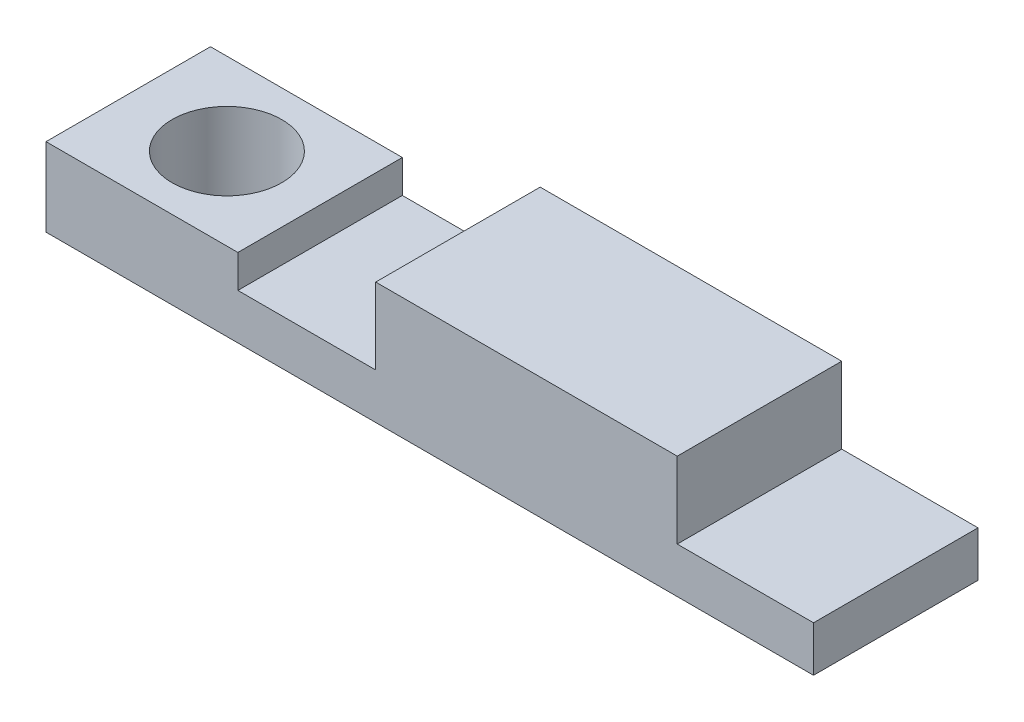
SolidWorks part; units mm, degrees
ref_plane "Front Plane" through (0, 0, 0) normal (0, 0, 1) x (1, 0, 0)
ref_plane "Top Plane" through (0, 0, 0) normal (0, 1, 0) x (1, 0, 0)
ref_plane "Right Plane" through (0, 0, 0) normal (1, 0, 0) x (0, 0, -1)
sketch "Sketch1" plane through (0, 0, 0) normal (0, 1, 0) x (1, 0, 0)
  line L1 (0, 0) -> (140, 0)
  line L2 (0, 0) -> (0, 30)
  line L3 (0, 30) -> (140, 30)
  line L4 (140, 0) -> (140, 30)
  dimension "D1" = 140
  dimension "D2" = 30
extrude "Boss-Extrude1" add sketch "Sketch1" along normal blind 8.3
sketch "Sketch3" plane through (0, 8.3, 0) normal (0, 1, 0) x (1, 0, 0)
  line L0 (140, 30) -> (0, 30) construction
  line L1 (0, 0) -> (35, 0)
  line L2 (0, 0) -> (0, 30)
  line L3 (0, 30) -> (35, 30)
  line L4 (35, 0) -> (35, 30)
  dimension "D1" = 35
extrude "Boss-Extrude2" add sketch "Sketch3" along normal blind 6
sketch "Sketch2" plane through (0, 8.3, 0) normal (0, 1, 0) x (1, 0, 0)
  line L0 (0, 15) -> (140, 15) construction
  line L1 (0, 30) -> (0, 0) construction
  line L2 (140, 0) -> (140, 30) construction
  circle A0 centre (18, 15) radius 10
  circle A1 centre (80.14, 15) radius 10
  dimension "D1" = 20
  dimension "D2" = 18
  dimension "D3" = 20
  dimension "D4" = 62.14
extrude "Cut-Extrude1" cut sketch "Sketch2" against normal blind 8.3 and the other way blind 6
sketch "Sketch4" plane through (0, 8.3, 0) normal (0, 1, 0) x (1, 0, 0)
  line L0 (140, 30) -> (35, 30) construction
  line L1 (60.14, 30) -> (115.14, 30)
  line L2 (60.14, 30) -> (60.14, 0)
  line L3 (60.14, 0) -> (115.14, 0)
  line L4 (115.14, 30) -> (115.14, 0)
  line L5 (35, 0) -> (140, 0) construction
  line L6 (80.14, 15) -> (80.14, 25) construction
  line L7 (80.14, 25) -> (80.14, 5) construction
  circle A0 centre (80.14, 15) radius 10 construction
  dimension "D1" = 55
  dimension "D2" = 20
extrude "Boss-Extrude3" add sketch "Sketch4" along normal blind 3.89
sketch "Sketch5" plane through (0, 0, 0) normal (0, -1, 0) x (1, 0, 0)
  line L0 (70.14, -15) -> (90.14, -15) construction
  circle A0 centre (80.14, -15) radius 10 construction
  circle A1 centre (80.14, -15) radius 10 construction
  circle A2 centre (80.14, -15) radius 10
extrude "Cut-Extrude2" cut sketch "Sketch5" against normal through all
sketch "Sketch7" plane through (0, 12.19, 0) normal (0, 1, 0) x (1, 0, 0)
  line L0 (87.64, 30) -> (87.64, 0) construction
  line L1 (115.14, 30) -> (60.14, 30) construction
  line L2 (60.14, 0) -> (115.14, 0) construction
  line L4 (60.14, 30) -> (115.14, 30)
  line L5 (60.14, 30) -> (60.14, 0)
  line L6 (60.14, 0) -> (115.14, 0)
  line L7 (115.14, 30) -> (115.14, 0)
extrude "Boss-Extrude4" add sketch "Sketch7" along normal blind 10
